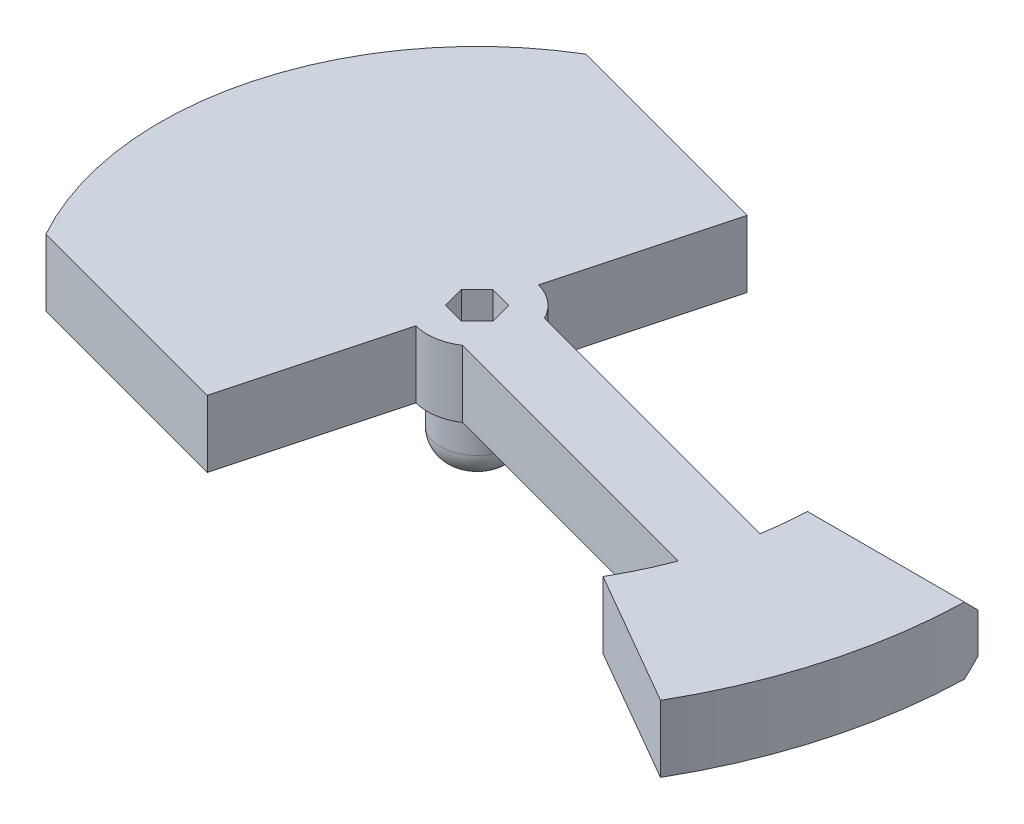
SolidWorks part; units mm, degrees
ref_plane "Front Plane" through (0, 0, 0) normal (0, 0, 1) x (1, 0, 0)
ref_plane "Top Plane" through (0, 0, 0) normal (0, 1, 0) x (1, 0, 0)
ref_plane "Right Plane" through (0, 0, 0) normal (1, 0, 0) x (0, 0, -1)
other "Center of Mass"
sketch "Sketch1" plane through (0, 0, 0) normal (0, 1, 0) x (1, 0, 0)
  line L0 (80.3219, 0) -> (95.25, 0) construction
  line L1 (80.3219, 0) -> (65.3937, 0) construction
  line L2 (65.3937, 0) -> (95.25, 0)
  line L3 (56.6326, -32.6969) -> (82.4889, -47.625)
  line L4 (0, 0) -> (9.1758, -2.5553) construction
  line L5 (92.0044, -24.6525) -> (0, 0) construction
  line L6 (8.5011, 4.2961) -> (64.5105, -10.7115)
  line L7 (5.2141, -7.9711) -> (61.2235, -22.9788)
  line L9 (-52.7582, -29.2519) -> (-10.8471, -40.482)
  line L10 (-10.8471, -40.482) -> (-2.4653, -9.2004)
  line L11 (10.8471, 40.482) -> (-31.064, 51.712)
  line L12 (0, 0) -> (-39.3939, 10.5556) construction
  line L13 (2.4653, 9.2004) -> (10.8471, 40.482)
  circle A0 centre (0, 0) radius 3.81
  circle A1 centre (0, 0) radius 101.6 construction
  arc A2 (82.4889, -47.625) -> (95.25, 0) centre (0, 0) ccw
  arc A4 (56.6326, -32.6969) -> (61.2235, -22.9788) centre (0, 0) ccw
  circle A5 centre (80.3219, 19.05) radius 19.05 construction
  arc A6 (8.5011, 4.2961) -> (2.4653, 9.2004) centre (0, 0) ccw
  arc A7 (9.1758, -2.5553) -> (9.2004, -2.4653) centre (0, 0) ccw
  arc A8 (64.5105, -10.7115) -> (65.3937, 0) centre (0, 0) ccw
  circle A9 centre (-57.4347, 59.2938) radius 19.05 construction
  arc A10 (-2.4653, -9.2004) -> (5.2141, -7.9711) centre (0, 0) ccw
  circle A11 centre (0, 0) radius 60.325 construction
  arc A12 (-31.064, 51.712) -> (-52.7582, -29.2519) centre (0, 0) ccw
  point P7 (80.3219, 0)
  dimension "D1" = 7.62
  dimension "D2" = 203.2
  dimension "D3" = 6.35
  dimension "D4" = 38.1
  dimension "D6" = 19.05
  dimension "D8" = 38.1
  dimension "D11" = 120.65
  dimension "D5" = 30
  dimension "D7" = 12.7
  dimension "D9" = 83.82
extrude "Boss-Extrude1" add sketch "Sketch1" along normal blind 12.7
sketch "Sketch2" plane through (0, 0, 0) normal (0, 0, 1) x (1, 0, 0)
  line L1 (6.985, 0) -> (0, 0)
  line L3 (6.985, -7.112) -> (6.985, 0)
  line L6 (1.905, -12.192) -> (0, -12.192)
  line L7 (0, -12.192) -> (0, 0)
  arc A0 (1.905, -12.192) -> (6.985, -7.112) centre (1.905, -7.112) ccw
  dimension "D1" = 5.08
  dimension "D2" = 12.192
  dimension "D3" = 6.985
revolve "Revolve1" add sketch "Sketch2" angle 360 about L7
sketch "Sketch5" plane through (0, 12.7, 0) normal (0, 1, 0) x (1, 0, 0)
  line L1 (3.0072, 3.0072) -> (-1.1007, 4.1079)
  line L2 (-1.1007, 4.1079) -> (-4.1079, 1.1007)
  line L3 (-4.1079, 1.1007) -> (-3.0072, -3.0072)
  line L4 (-3.0072, -3.0072) -> (1.1007, -4.1079)
  line L5 (1.1007, -4.1079) -> (4.1079, -1.1007)
  line L6 (4.1079, -1.1007) -> (3.0072, 3.0072)
  line L8 (8.5011, 4.2961) -> (64.5105, -10.7115) construction
  circle A0 centre (0, 0) radius 3.683 construction
  dimension "D1" = 7.366
extrude "Cut-Extrude2" cut sketch "Sketch5" against normal blind 15.24
chamfer "Chamfer1" distance 2.54 angle 45 2 edges at (80.3219, 0, 0) (80.3219, 12.7, 0)
